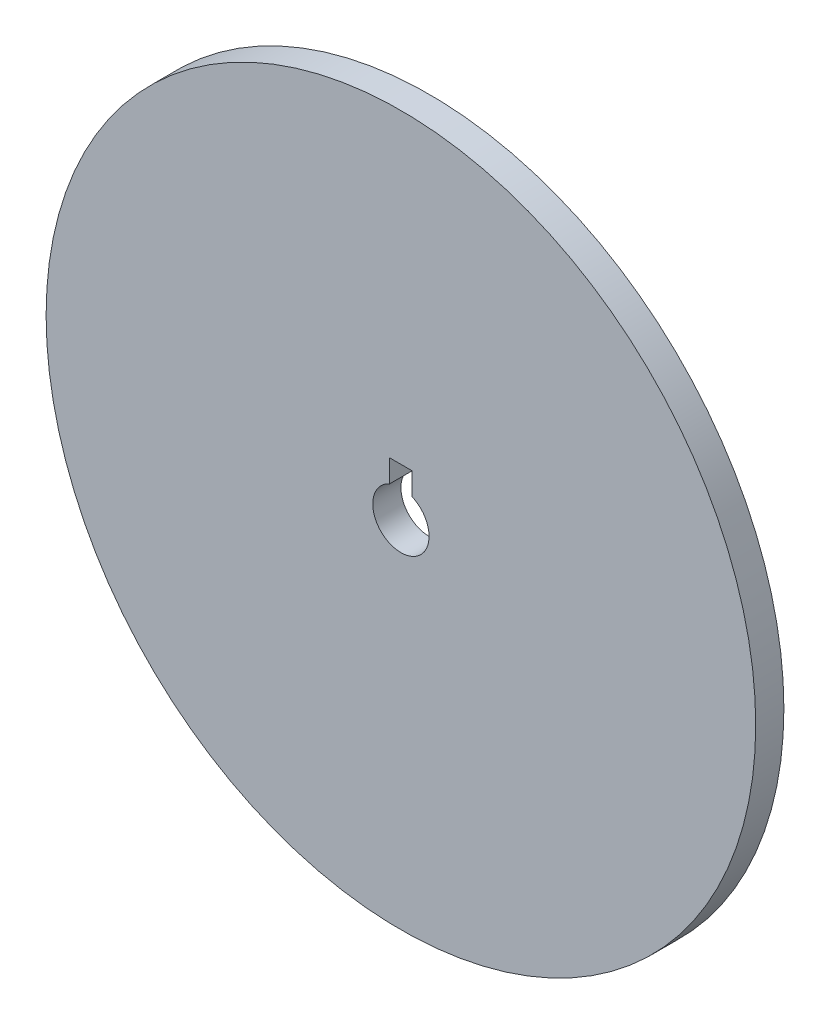
SolidWorks part; units mm, degrees
ref_plane "Ön Düzlem" through (0, 0, 0) normal (0, 0, 1) x (1, 0, 0)
ref_plane "Üst Düzlem" through (0, 0, 0) normal (0, 1, 0) x (1, 0, 0)
ref_plane "Sağ Düzlem" through (0, 0, 0) normal (1, 0, 0) x (0, 0, -1)
sketch "Çizim1" plane through (0, 0, 0) normal (0, 0, 1) x (1, 0, 0)
  circle A0 centre (0, 0) radius 63
  dimension "D1" = 126
extrude "Yükseklik-Ekstrüzyon1" add sketch "Çizim1" along normal blind 5
sketch "Çizim2" plane through (0, 0, 5) normal (0, 0, 1) x (1, 0, 0)
  circle A0 centre (0, 0) radius 5
  dimension "D1" = 10
extrude "Kes-Ekstrüzyon1" cut sketch "Çizim2" against normal blind 10
sketch "Çizim3" plane through (0, 0, 0) normal (0, 0, -1) x (-1, 0, 0)
  line L1 (-2, 8.5826) -> (2, 8.5826)
  line L2 (-2, 8.5826) -> (-2, 4.5826)
  line L3 (-2, 4.5826) -> (2, 4.5826)
  line L4 (2, 8.5826) -> (2, 4.5826)
  circle A0 centre (0, 0) radius 5 construction
  dimension "D1" = 2
  dimension "D2" = 2
  dimension "D3" = 4
extrude "Kes-Ekstrüzyon2" cut sketch "Çizim3" against normal blind 8 contours L2 L1 L4 L3
